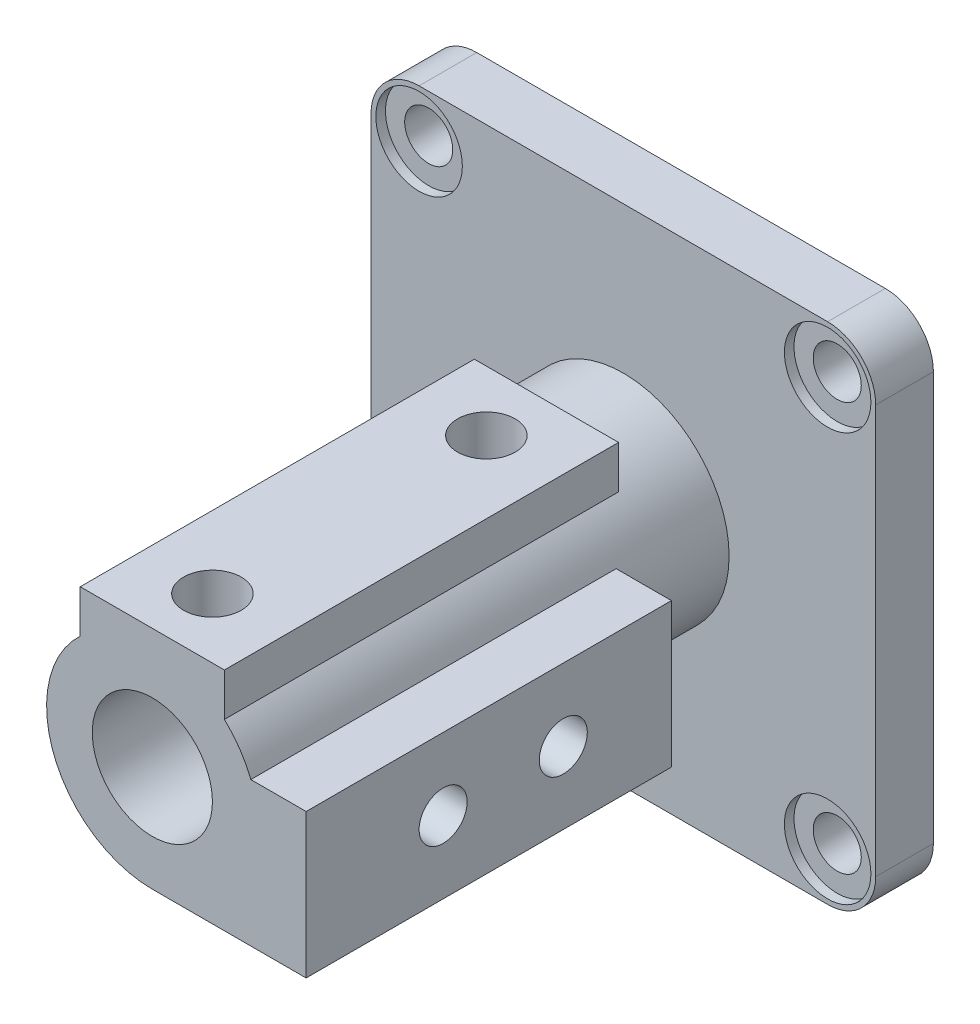
SolidWorks part; units mm, degrees
ref_plane "Front Plane" through (0, 0, 0) normal (0, 0, 1) x (1, 0, 0)
ref_plane "Top Plane" through (0, 0, 0) normal (0, 1, 0) x (1, 0, 0)
ref_plane "Right Plane" through (0, 0, 0) normal (1, 0, 0) x (0, 0, -1)
sketch "Sketch1" plane through (0, 0, 0) normal (0, 0, 1) x (1, 0, 0)
  line L1 (-52.5, 52.5) -> (52.5, 52.5)
  line L2 (-52.5, 52.5) -> (-52.5, -52.5)
  line L3 (-52.5, -52.5) -> (52.5, -52.5)
  line L4 (52.5, 52.5) -> (52.5, -52.5)
  line L5 (-52.5, 52.5) -> (52.5, -52.5) construction
  line L6 (-52.5, -52.5) -> (52.5, 52.5) construction
  point P0 (0, 0)
  dimension "D1" = 105
  dimension "D2" = 105
extrude "Boss-Extrude1" add sketch "Sketch1" along normal blind 12
sketch "Sketch2" plane through (0, 0, 12) normal (0, 0, 1) x (1, 0, 0)
  circle A0 centre (0, 0) radius 22
  dimension "D1" = 44
extrude "Boss-Extrude2" add sketch "Sketch2" along normal blind 98
sketch "Sketch3" plane through (0, 0, 110) normal (0, 0, 1) x (1, 0, 0)
  line L0 (-15, 16.0935) -> (-15, 25)
  line L1 (-15, 25) -> (15, 25)
  line L2 (15, 25) -> (15, 16.0935)
  line L3 (0, 0) -> (0, 41.8138) construction
  circle A3 centre (0, 0) radius 22 construction
  arc A4 (15, 16.0935) -> (-15, 16.0935) centre (0, 0) ccw
  point P10 (0, 0)
  point P11 (21.174, 5.9719)
  point P12 (0, 0)
  point P13 (0, 0)
  point P14 (15, 10.9941)
  dimension "D1" = 30
  dimension "D2" = 25
extrude "Boss-Extrude3" add sketch "Sketch3" against normal blind 82
hole_wizard "Hole1" positions "Sketch4" profile "Sketch5" legacy end condition through all
sketch "Sketch4" plane through (0, 0, 110) normal (0, 0, 1) x (1, 0, 0)
  point P0 (0, 0)
sketch "Sketch5" plane through (0, 0, 110) normal (1, 0, 0) x (0, -1, 0)
  line L0 (0, 0) -> (0, 110)
  line L1 (0, 110) -> (12.5, 110)
  line L2 (12.5, 110) -> (12.5, 0)
  line L3 (12.5, 0) -> (0, 0)
  line L4 (0, 110) -> (0, -10) construction
  dimension "Diameter" = 25
  dimension "Depth" = 110
hole_wizard "Hole2" positions "Sketch6" profile "Sketch7" legacy
sketch "Sketch6" plane through (0, 25, 0) normal (0, 1, 0) x (1, 0, 0)
  line L0 (-15, -69) -> (54.3688, -69) construction
  line L1 (-15, -28) -> (-15, -110) construction
  point P0 (0, -40.5)
  point P2 (0, -97.5)
  point P10 (0, 0)
  point P11 (0, 0)
  dimension "D1" = 57
sketch "Sketch7" plane through (0, 25, 40.5) normal (1, 0, 0) x (0, 0, 1)
  line L0 (0, 0) -> (0, 12.5)
  line L1 (0, 12.5) -> (6, 12.5)
  line L2 (6, 12.5) -> (6, 0)
  line L3 (6, 0) -> (0, 0)
  line L4 (0, 110) -> (0, -10) construction
  dimension "Diameter" = 12
  dimension "Depth" = 12.5
sketch "Sketch9" plane through (0, 0, 110) normal (0, 0, 1) x (1, 0, 0)
  line L0 (0, -22) -> (32, -22)
  line L1 (32, -22) -> (32, 8)
  line L2 (32, 8) -> (20.4939, 8)
  circle A0 centre (0, 0) radius 22 construction
  arc A1 (0, -22) -> (20.4939, 8) centre (0, 0) ccw
  point P5 (20.6659, 7.5447)
  dimension "D1" = 32
  dimension "D2" = 30
extrude "Boss-Extrude4" add sketch "Sketch9" against normal blind 76
hole_wizard "Hole3" positions "Sketch10" profile "Sketch11" legacy
sketch "Sketch10" plane through (32, 0, 0) normal (1, 0, 0) x (0, 0, -1)
  line L0 (-34, 8) -> (-110, 8) construction
  line L1 (-69, 25) -> (-69, -43.5616) construction
  line L2 (-28, 25) -> (-110, 25) construction
  point P0 (-81.5, -7)
  point P2 (-56.5, -7)
  point P13 (0, 0)
  dimension "D1" = 25
  dimension "D2" = 15
sketch "Sketch11" plane through (32, -7, 81.5) normal (0, 1, 0) x (0, 0, -1)
  line L0 (0, 0) -> (0, 21.6438)
  line L1 (0, 21.6438) -> (5, 21.6438)
  line L2 (5, 21.6438) -> (5, 0)
  line L3 (5, 0) -> (0, 0)
  line L4 (0, 110) -> (0, -10) construction
  dimension "Diameter" = 10
  dimension "Depth" = 21.6438
fillet "Fillet1" radius 10 4 edges at (-52.5, -52.5, 6) (52.5, -52.5, 6) (-52.5, 52.5, 6) (52.5, 52.5, 6)
hole_wizard "Hole4" positions "Sketch12" profile "Sketch13" legacy end condition up to next
sketch "Sketch12" plane through (0, 0, 12) normal (0, 0, 1) x (1, 0, 0)
  point P0 (42.5, -42.5)
  point P3 (42.5, 42.5)
  point P6 (-42.5, 42.5)
  point P9 (-42.5, -42.5)
sketch "Sketch13" plane through (42.5, -42.5, 12) normal (1, 0, 0) x (0, -1, 0)
  line L0 (0, 0) -> (0, 12)
  line L1 (0, 12) -> (5, 12)
  line L2 (5, 12) -> (5, 2)
  line L3 (5, 2) -> (9, 2)
  line L4 (9, 2) -> (9, 0)
  line L5 (9, 0) -> (0, 0)
  line L6 (0, 110) -> (0, -10) construction
  dimension "Diameter" = 10
  dimension "Depth" = 12
  dimension "C-Bore Diameter" = 18
  dimension "C-Bore Depth" = 2
